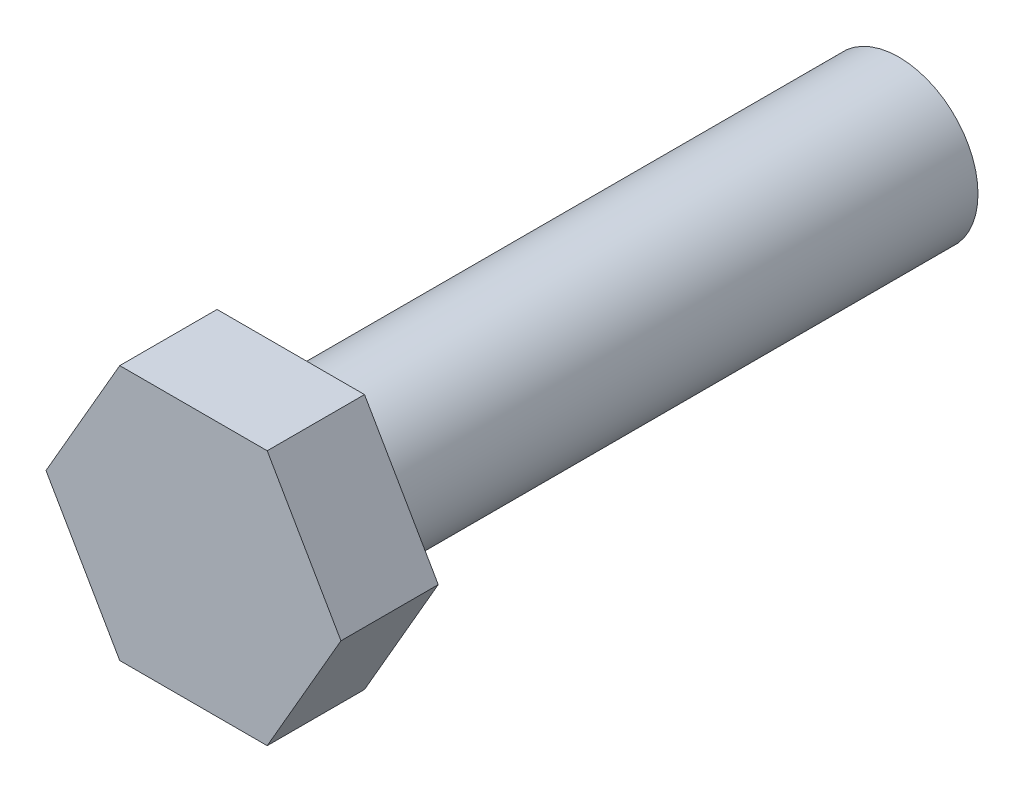
SolidWorks part; units mm, degrees
ref_plane "Front Plane" through (0, 0, 0) normal (0, 0, 1) x (1, 0, 0)
ref_plane "Top Plane" through (0, 0, 0) normal (0, 1, 0) x (1, 0, 0)
ref_plane "Right Plane" through (0, 0, 0) normal (1, 0, 0) x (0, 0, -1)
sketch "Sketch1" plane through (0, 0, 0) normal (0, 0, 1) x (1, 0, 0)
  line L1 (30.7959, 0) -> (15.3979, 26.67)
  line L2 (15.3979, 26.67) -> (-15.3979, 26.67)
  line L3 (-15.3979, 26.67) -> (-30.7959, 0)
  line L4 (-30.7959, 0) -> (-15.3979, -26.67)
  line L5 (-15.3979, -26.67) -> (15.3979, -26.67)
  line L6 (15.3979, -26.67) -> (30.7959, 0)
  circle A0 centre (0, 0) radius 26.67 construction
  dimension "D1" = 53.34
extrude "Boss-Extrude1" add sketch "Sketch1" along normal blind 20.32
sketch "Sketch2" plane through (0, 0, 0) normal (0, 0, -1) x (-1, 0, 0)
  circle A0 centre (0, 0) radius 16.51
  dimension "D1" = 33.02
extrude "Boss-Extrude2" add sketch "Sketch2" along normal blind 127
